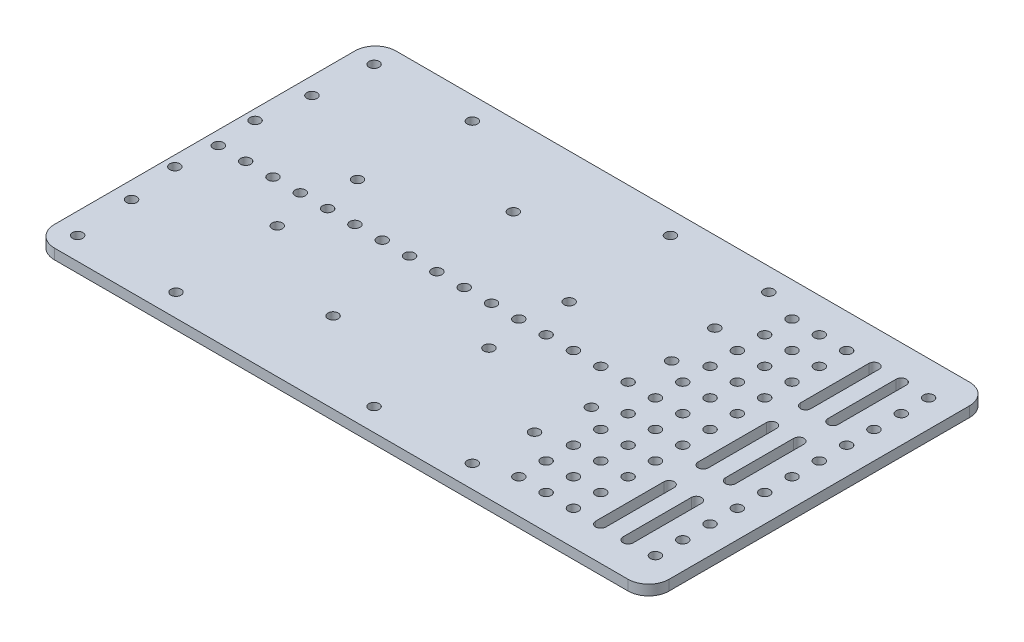
SolidWorks part; units mm, degrees
ref_plane "Front Plane" through (0, 0, 0) normal (0, 0, 1) x (1, 0, 0)
ref_plane "Top Plane" through (0, 0, 0) normal (0, 1, 0) x (1, 0, 0)
ref_plane "Right Plane" through (0, 0, 0) normal (1, 0, 0) x (0, 0, -1)
sketch "Sketch2" plane through (0, 0, 0) normal (0, 1, 0) x (1, 0, 0)
  line L1 (90, 50) -> (-90, 50)
  line L2 (90, 50) -> (90, -50)
  line L3 (90, -50) -> (-90, -50)
  line L4 (-90, 50) -> (-90, -50)
  line L5 (90, 50) -> (-90, -50) construction
  line L6 (90, -50) -> (-90, 50) construction
  point P0 (0, 0)
  dimension "D1" = 180
  dimension "D2" = 100
extrude "Boss-Extrude1" add sketch "Sketch2" along normal blind 3
sketch "Sketch3" plane through (0, 3, 0) normal (0, 1, 0) x (1, 0, 0)
  line L0 (-90, 0) -> (90, 0) construction
  line L1 (-90, 50) -> (-90, -50) construction
  line L2 (90, -50) -> (90, 50) construction
  line L3 (0, 50) -> (0, -50) construction
  line L4 (90, 50) -> (-90, 50) construction
  line L5 (-90, -50) -> (90, -50) construction
  line L7 (-57, -11.75) -> (-87, -11.75) construction
  line L8 (-57, -11.75) -> (-57, 11.75) construction
  line L9 (-57, 11.75) -> (-87, 11.75) construction
  line L10 (-87, -11.75) -> (-87, 11.75) construction
  line L11 (-57, -11.75) -> (-87, 11.75) construction
  line L12 (-57, 11.75) -> (-87, -11.75) construction
  line L13 (31.8, -43.4) -> (-55, -43.4) construction
  line L14 (31.8, -43.4) -> (31.8, 43.4) construction
  line L15 (31.8, 43.4) -> (-55, 43.4) construction
  line L16 (-55, -43.4) -> (-55, 43.4) construction
  line L17 (31.8, -43.4) -> (-55, 43.4) construction
  line L18 (31.8, 43.4) -> (-55, -43.4) construction
  line L19 (-26, -26.4) -> (33, -26.4) construction
  line L20 (-26, -26.4) -> (-26, 26.4) construction
  line L21 (-26, 26.4) -> (33, 26.4) construction
  line L22 (33, -26.4) -> (33, 26.4) construction
  line L23 (-26, -26.4) -> (33, 26.4) construction
  line L24 (-26, 26.4) -> (33, -26.4) construction
  circle A0 centre (-57, 11.75) radius 1.5
  circle A1 centre (-87, 11.75) radius 1.5
  circle A2 centre (-87, -11.75) radius 1.5
  circle A3 centre (-57, -11.75) radius 1.5
  circle A4 centre (-55, 43.4) radius 1.5
  circle A5 centre (31.8, 43.4) radius 1.5
  circle A6 centre (31.8, -43.4) radius 1.5
  circle A7 centre (-55, -43.4) radius 1.5
  circle A8 centre (-26, -26.4) radius 1.5
  circle A9 centre (33, -26.4) radius 1.5
  circle A10 centre (33, 26.4) radius 1.5
  circle A11 centre (-26, 26.4) radius 1.5
  point P12 (-72, 0)
  point P21 (-11.6, 0)
  point P30 (3.5, 0)
  dimension "D4" = 3
  dimension "D5" = 86.8
  dimension "D8" = 3
  dimension "D12" = 3
  dimension "D1" = 30
  dimension "D2" = 23.5
  dimension "D3" = 3
  dimension "D6" = 86.8
  dimension "D7" = 35
  dimension "D9" = 59
  dimension "D10" = 52.8
  dimension "D11" = 64
extrude "Cut-Extrude1" cut sketch "Sketch3" against normal through all
sketch "Sketch6" plane through (0, 3, 0) normal (0, 1, 0) x (1, 0, 0)
  line L0 (0, 0) -> (90, 0) construction
  line L1 (90, -50) -> (90, 50) construction
  line L2 (74, 10) -> (74, -10) construction
  line L3 (75.5, 10) -> (75.5, -10)
  line L4 (72.5, 10) -> (72.5, -10)
  line L5 (74, 50) -> (74, -50) construction
  line L6 (90, 50) -> (-90, 50) construction
  line L7 (-90, -50) -> (90, -50) construction
  line L8 (74, -40) -> (74, -20) construction
  line L9 (72.5, -40) -> (72.5, -20)
  line L10 (75.5, -40) -> (75.5, -20)
  line L11 (74, 20) -> (74, 40) construction
  line L12 (72.5, 20) -> (72.5, 40)
  line L13 (75.5, 20) -> (75.5, 40)
  line L14 (66, 10) -> (66, -10) construction
  line L15 (67.5, 10) -> (67.5, -10)
  line L16 (64.5, 10) -> (64.5, -10)
  line L17 (66, -40) -> (66, -20) construction
  line L18 (64.5, -40) -> (64.5, -20)
  line L19 (67.5, -40) -> (67.5, -20)
  line L20 (66, 20) -> (66, 40) construction
  line L21 (64.5, 20) -> (64.5, 40)
  line L22 (67.5, 20) -> (67.5, 40)
  line L23 (66, 50) -> (66, -50) construction
  arc A0 (75.5, 10) -> (72.5, 10) centre (74, 10) ccw
  arc A1 (72.5, -10) -> (75.5, -10) centre (74, -10) ccw
  arc A2 (72.5, -40) -> (75.5, -40) centre (74, -40) ccw
  arc A3 (75.5, -20) -> (72.5, -20) centre (74, -20) ccw
  arc A4 (72.5, 20) -> (75.5, 20) centre (74, 20) ccw
  arc A5 (75.5, 40) -> (72.5, 40) centre (74, 40) ccw
  arc A6 (67.5, 10) -> (64.5, 10) centre (66, 10) ccw
  arc A7 (64.5, -10) -> (67.5, -10) centre (66, -10) ccw
  arc A8 (64.5, -40) -> (67.5, -40) centre (66, -40) ccw
  arc A9 (67.5, -20) -> (64.5, -20) centre (66, -20) ccw
  arc A10 (64.5, 20) -> (67.5, 20) centre (66, 20) ccw
  arc A11 (67.5, 40) -> (64.5, 40) centre (66, 40) ccw
  point P7 (74, 0)
  point P20 (74, -30)
  point P27 (74, 30)
  point P35 (66, 0)
  point P42 (66, -30)
  point P49 (66, 30)
  dimension "D1" = 1.5
  dimension "D4" = 1.5
  dimension "D7" = 1.5
  dimension "D2" = 20
  dimension "D3" = 16
  dimension "D5" = 30
  dimension "D6" = 20
  dimension "D8" = 20
  dimension "D9" = 30
  dimension "D11" = 8
  dimension "D10" = 2
extrude "Cut-Extrude2" cut sketch "Sketch6" against normal through all
sketch "Sketch7" plane through (0, 3, 0) normal (0, 1, 0) x (1, 0, 0)
  line L0 (90, 0) -> (0, 0) construction
  line L1 (90, -50) -> (90, 50) construction
  circle A0 centre (82, 0) radius 1.5
  circle A1 centre (58, 0) radius 1.5
  circle A2 centre (50, 0) radius 1.5
  circle A3 centre (42, 0) radius 1.5
  circle A4 centre (34, 0) radius 1.5
  circle A5 centre (26, 0) radius 1.5
  circle A6 centre (18, 0) radius 1.5
  circle A7 centre (10, 0) radius 1.5
  circle A8 centre (2, 0) radius 1.5
  circle A9 centre (-6, 0) radius 1.5
  circle A10 centre (-14, 0) radius 1.5
  circle A11 centre (-22, 0) radius 1.5
  circle A12 centre (-30, 0) radius 1.5
  circle A13 centre (-38, 0) radius 1.5
  circle A14 centre (-46, 0) radius 1.5
  circle A15 centre (-54, 0) radius 1.5
  circle A16 centre (-62, 0) radius 1.5
  circle A17 centre (-70, 0) radius 1.5
  circle A18 centre (-78, 0) radius 1.5
  circle A19 centre (-86, 0) radius 1.5
  circle A20 centre (42, 8) radius 1.5
  circle A21 centre (50, 8) radius 1.5
  circle A22 centre (58, 8) radius 1.5
  circle A23 centre (82, 8) radius 1.5
  circle A24 centre (42, 16) radius 1.5
  circle A25 centre (50, 16) radius 1.5
  circle A26 centre (58, 16) radius 1.5
  circle A27 centre (82, 16) radius 1.5
  circle A28 centre (42, 24) radius 1.5
  circle A29 centre (50, 24) radius 1.5
  circle A30 centre (58, 24) radius 1.5
  circle A31 centre (82, 24) radius 1.5
  circle A32 centre (42, 32) radius 1.5
  circle A33 centre (50, 32) radius 1.5
  circle A34 centre (58, 32) radius 1.5
  circle A35 centre (82, 32) radius 1.5
  circle A36 centre (42, 40) radius 1.5
  circle A37 centre (50, 40) radius 1.5
  circle A38 centre (58, 40) radius 1.5
  circle A39 centre (82, 40) radius 1.5
  circle A40 centre (42, -8) radius 1.5
  circle A41 centre (50, -8) radius 1.5
  circle A42 centre (58, -8) radius 1.5
  circle A43 centre (82, -8) radius 1.5
  circle A44 centre (42, -16) radius 1.5
  circle A45 centre (50, -16) radius 1.5
  circle A46 centre (58, -16) radius 1.5
  circle A47 centre (82, -16) radius 1.5
  circle A48 centre (42, -24) radius 1.5
  circle A49 centre (50, -24) radius 1.5
  circle A50 centre (58, -24) radius 1.5
  circle A51 centre (82, -24) radius 1.5
  circle A52 centre (42, -32) radius 1.5
  circle A53 centre (50, -32) radius 1.5
  circle A54 centre (58, -32) radius 1.5
  circle A55 centre (82, -32) radius 1.5
  circle A56 centre (42, -40) radius 1.5
  circle A57 centre (50, -40) radius 1.5
  circle A58 centre (58, -40) radius 1.5
  circle A59 centre (82, -40) radius 1.5
  dimension "D1" = 3
  dimension "D2" = 8
  dimension "D3" = 32
  dimension "D4" = 19
  dimension "D5" = 6
  dimension "D6" = 6
extrude "Cut-Extrude3" cut sketch "Sketch7" against normal through all
ref_plane "Plane1" through (-26, 0, 0) normal (-1, 0, 0) x (0, 0, 1)
mirror "Mirror2" about plane through (-26, 0, 0) normal (-1, 0, 0) of "Cut-Extrude1"
fillet "Fillet1" radius 6 4 edges at (90, 1.5, -50) (90, 1.5, 50) (-90, 1.5, 50) (-90, 1.5, -50)
